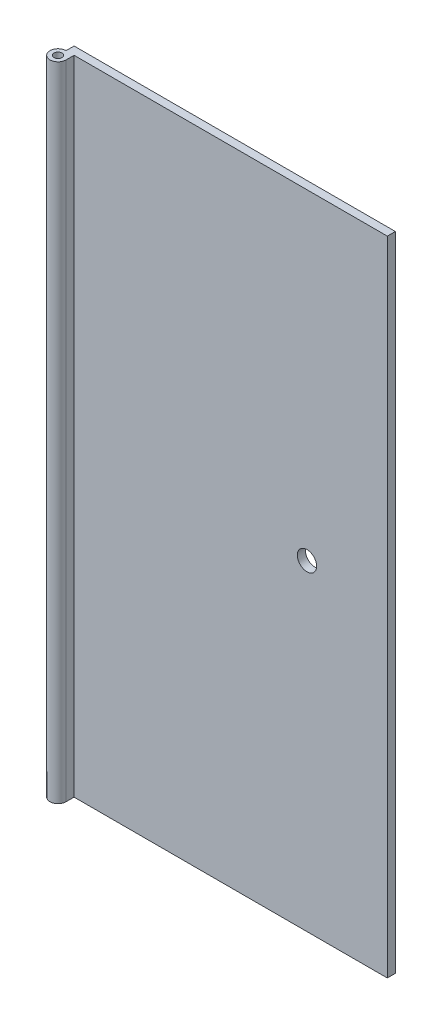
SolidWorks part; units mm, degrees
ref_plane "Plan de face" through (0, 0, 0) normal (0, 0, 1) x (1, 0, 0)
ref_plane "Plan de dessus" through (0, 0, 0) normal (0, 1, 0) x (1, 0, 0)
ref_plane "Plan de droite" through (0, 0, 0) normal (1, 0, 0) x (0, 0, -1)
sketch "Esquisse1" plane through (0, 0, 0) normal (0, 0, 1) x (1, 0, 0)
  line L1 (0, 0) -> (40, 0)
  line L2 (0, 0) -> (0, 80)
  line L3 (0, 80) -> (40, 80)
  line L4 (40, 0) -> (40, 80)
  dimension "D1" = 40
  dimension "D2" = 80
extrude "Boss.-Extru.1" add sketch "Esquisse1" along normal blind 1
sketch "Esquisse2" plane through (0, 80, 0) normal (0, 1, 0) x (1, 0, 0)
  line L0 (1, 0) -> (1, 1)
  line L1 (40, 0) -> (0, 0) construction
  line L2 (0, 1) -> (0, 0) construction
  line L3 (1, 0) -> (0, 0)
  arc A0 (0, 0) -> (1, 1) centre (0, 1) cw
  circle A1 centre (0, 1) radius 0.5
  dimension "D1" = 1
  dimension "D2" = 1
  dimension "D3" = 1
extrude "Boss.-Extru.2" add sketch "Esquisse2" against normal up to surface (80 mm away) up to face at (20, 0, 0.5)
ref_plane "Plan2" through (0, 0, 1) normal (0, 0, 1) x (1, 0, 0)
mirror "Symétrie2" about plane through (0, 0, 1) normal (0, 0, 1) of "Boss.-Extru.2", "Boss.-Extru.1"
sketch "Esquisse3" plane through (40, 0, 0) normal (1, 0, 0) x (0, 0, -1)
  line L0 (-2, 80) -> (0, 80) construction
  line L1 (2, 0) -> (-1, 0)
  line L2 (2, 0) -> (2, 80)
  line L3 (2, 80) -> (-1, 80)
  line L4 (-1, 0) -> (-1, 80)
extrude "Enlèv. mat.-Extru.1" cut sketch "Esquisse3" against normal through all
hole_wizard "Dégagement M21" positions "Esquisse5" profile "Esquisse6" hole size "M2" standard "ISO"
sketch "Esquisse5" plane through (0, 0, 2) normal (0, 0, 1) x (1, 0, 0)
  line L0 (40, 40) -> (30, 40) construction
  line L1 (40, 0) -> (40, 80) construction
  point P0 (30, 40)
  dimension "D1" = 10
sketch "Esquisse6" plane through (30, 40, 2) normal (1, 0, 0) x (0, -1, 0)
  line L0 (0, 0) -> (0, 1.72)
  line L1 (0, 1.72) -> (1.2, 0.999)
  line L2 (1.2, 0.999) -> (1.2, 0)
  line L5 (1.2, 0) -> (0, 0)
  line L10 (0, 1.72) -> (-1.2, 0.999) construction
  line L11 (0, -6.35) -> (0, 107.95) construction
  dimension "Diamètre du perçage" = 2.4
  dimension "Profondeur du perçage" = 0.999
  dimension "Angle de pointe" = 118
